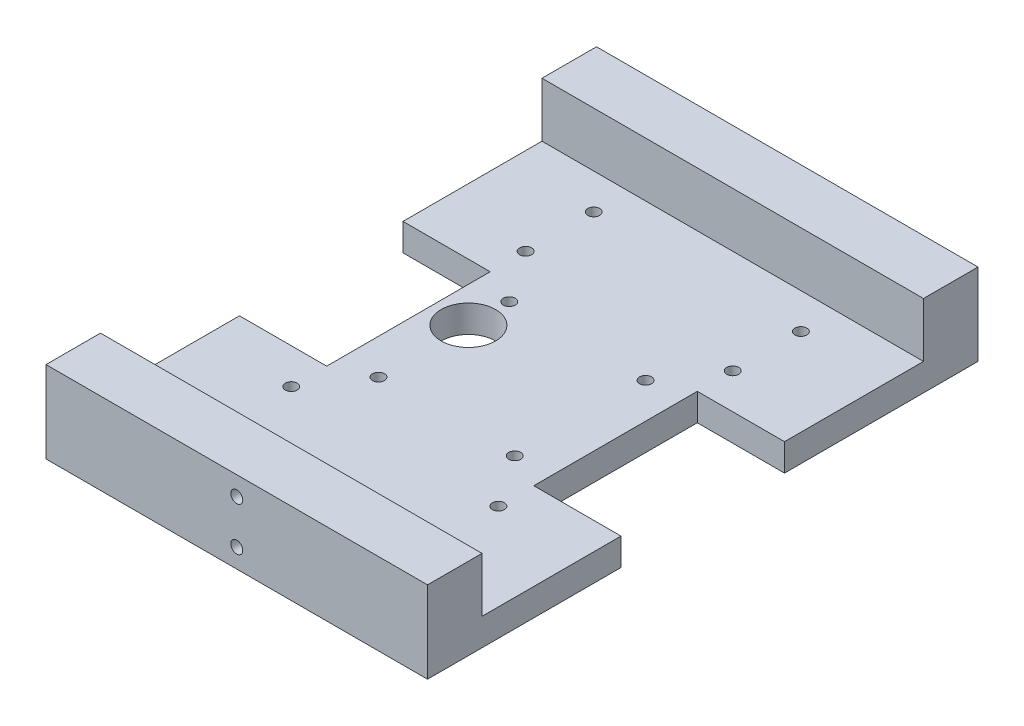
SolidWorks part; units mm, degrees
ref_plane "前基準面" through (0, 0, 0) normal (0, 0, 1) x (1, 0, 0)
ref_plane "上基準面" through (0, 0, 0) normal (0, 1, 0) x (1, 0, 0)
ref_plane "右基準面" through (0, 0, 0) normal (1, 0, 0) x (0, 0, -1)
sketch "草圖1" plane through (0, 0, 0) normal (0, 1, 0) x (1, 0, 0)
  line L1 (-35, -50.5) -> (35, -50.5)
  line L2 (-35, -50.5) -> (-35, 50.5)
  line L3 (-35, 50.5) -> (35, 50.5)
  line L4 (35, -50.5) -> (35, 50.5)
  line L5 (-35, -50.5) -> (35, 50.5) construction
  line L6 (-35, 50.5) -> (35, -50.5) construction
  point P0 (0, 0)
  dimension "D1" = 70
  dimension "D2" = 101
extrude "填料-伸長1" add sketch "草圖1" along normal blind 15
sketch "草圖2" plane through (0, 15, 0) normal (0, 1, 0) x (1, 0, 0)
  circle A0 centre (0, 0) radius 8
  dimension "D1" = 16
extrude "除料-伸長1" [suppressed] cut sketch "草圖2" against normal through all
sketch "草圖3" plane through (0, 15, 0) normal (0, 1, 0) x (1, 0, 0)
  line L0 (-35, 50.5) -> (-35, -50.5) construction
  line L1 (35, -40.5) -> (-35, -40.5)
  line L2 (35, -40.5) -> (35, 40.5)
  line L3 (35, 40.5) -> (-35, 40.5)
  line L4 (-35, -40.5) -> (-35, 40.5)
  line L5 (35, -40.5) -> (-35, 40.5) construction
  line L6 (35, 40.5) -> (-35, -40.5) construction
  line L7 (-35, -50.5) -> (35, -50.5) construction
  point P0 (0, 0)
  dimension "D1" = 10
extrude "除料-伸長2" cut sketch "草圖3" against normal blind 10
hole_wizard "Ø1.0mm 定位孔1" positions "草圖4" profile "草圖6" hole size "Ø1.0" standard "ISO"
sketch "草圖4" plane through (0, 0, -50.5) normal (0, 0, -1) x (-1, 0, 0)
  line L0 (-35, 0) -> (35, 0) construction
  point P0 (0, 3.5)
  point P2 (0, 11.5)
  dimension "D1" = 8
  dimension "D2" = 3.5
sketch "草圖6" plane through (0, 3.5, -50.5) normal (1, 0, 0) x (0, 1, 0)
  line L0 (0, 0) -> (0, 7.0109)
  line L1 (0, 7.0109) -> (1.1, 6.35)
  line L2 (1.1, 6.35) -> (1.1, 0)
  line L5 (1.1, 0) -> (0, 0)
  line L10 (0, 7.0109) -> (-1.1, 6.35) construction
  line L11 (0, -6.35) -> (0, 107.95) construction
  dimension "鑽孔直徑" = 2.2
  dimension "鑽孔深度" = 6.35
  dimension "導頭角度" = 118
mirror "鏡射1" about plane through (0, 0, 0) normal (0, 0, 1) of "Ø1.0mm 定位孔1"
sketch "草圖7" plane through (0, 5, 0) normal (0, 1, 0) x (1, 0, 0)
  line L0 (35, -40.5) -> (35, 40.5) construction
  line L1 (35, 15) -> (19, 15)
  line L2 (35, 15) -> (35, -15)
  line L3 (35, -15) -> (19, -15)
  line L4 (19, 15) -> (19, -15)
  line L5 (19, 0) -> (0, 0) construction
  dimension "D1" = 30
  dimension "D2" = 16
extrude "除料-伸長3" cut sketch "草圖7" against normal through all
mirror "鏡射2" about plane through (0, 0, 0) normal (1, 0, 0) of "除料-伸長3"
sketch "草圖8" [suppressed] plane through (0, 0, 0) normal (1, 0, 0) x (0, 0, -1)
  line L0 (0, 0) -> (0, 80)
  dimension "D1" = 80
hole_wizard "Ø1.0mm 定位孔3" positions "草圖9" profile "草圖10" hole size "Ø1.0" standard "ISO" end condition up to next
sketch "草圖9" plane through (0, 0, 0) normal (0, -1, 0) x (-1, 0, 0)
  line L0 (-12.5, -12) -> (12.5, 12) construction
  line L2 (-12.5, 12) -> (12.5, -12) construction
  point P0 (-12.5, -12)
  point P2 (12.5, -12)
  point P4 (-12.5, 12)
  point P6 (12.5, 12)
  dimension "D1" = 24
  dimension "D2" = 25
sketch "草圖10" plane through (12.5, 0, 12) normal (1, 0, 0) x (0, 0, -1)
  line L0 (0, 0) -> (0, 5)
  line L1 (0, 5) -> (1.1, 5)
  line L2 (1.1, 5) -> (1.1, 0)
  line L5 (1.1, 0) -> (0, 0)
  line L11 (0, -6.35) -> (0, 107.95) construction
  dimension "貫穿孔直徑" = 2.2
  dimension "貫穿孔深度" = 5
sketch "草圖11" plane through (0, 0, 0) normal (0, -1, 0) x (1, 0, 0)
  line L1 (-12.5, -15) -> (12.5, -15) construction
  line L2 (-12.5, -15) -> (-12.5, 15) construction
  line L3 (-12.5, 15) -> (12.5, 15) construction
  line L4 (12.5, -15) -> (12.5, 15) construction
  line L5 (-12.5, -15) -> (12.5, 15) construction
  line L6 (-12.5, 15) -> (12.5, -15) construction
  circle A0 centre (-12.5, -4.5) radius 5
  point P0 (0, 0)
  dimension "D3" = 10.5
  dimension "D4" = 10
  dimension "D1" = 30
  dimension "D2" = 25
extrude "除料-伸長4" cut sketch "草圖11" against normal through all
hole_wizard "Ø1.0mm 定位孔2" positions "草圖12" profile "草圖14" hole size "Ø1.0" standard "ISO" end condition through all
sketch "草圖12" plane through (0, 5, 0) normal (0, 1, 0) x (1, 0, 0)
  line L1 (35, 15) -> (35, 40.5) construction
  line L2 (35, 40.5) -> (-35, 40.5) construction
  line L3 (35, 15) -> (19, 15) construction
  line L4 (-35, 40.5) -> (-35, 15) construction
  point P0 (-19, 34)
  point P2 (-19, 21.5)
  point P4 (19, 21.5)
  point P6 (19, 34)
  dimension "D1" = 16
  dimension "D2" = 6.5
  dimension "D3" = 6.5
  dimension "D4" = 16
sketch "草圖14" plane through (-19, 5, -34) normal (1, 0, 0) x (0, 0, 1)
  line L0 (0, 0) -> (0, 5)
  line L1 (0, 5) -> (1.1, 5)
  line L2 (1.1, 5) -> (1.1, 0)
  line L5 (1.1, 0) -> (0, 0)
  line L11 (0, -6.35) -> (0, 107.95) construction
  dimension "貫穿孔直徑" = 2.2
  dimension "貫穿孔深度" = 5
mirror "鏡射3" about plane through (0, 0, 0) normal (0, 0, 1) of "Ø1.0mm 定位孔2"
